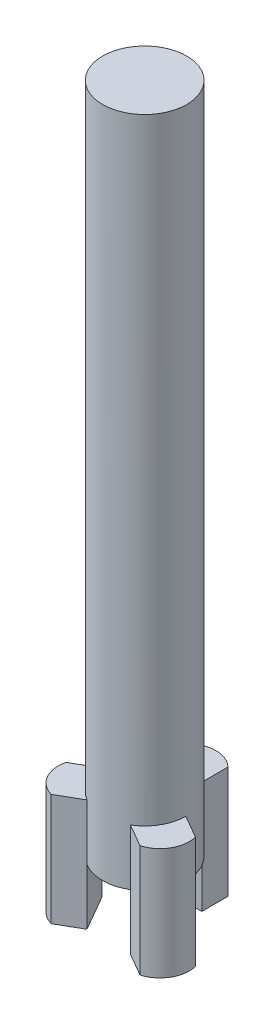
SolidWorks part; units mm, degrees
ref_plane "Plan de face" through (0, 0, 0) normal (0, 0, 1) x (1, 0, 0)
ref_plane "Plan de dessus" through (0, 0, 0) normal (0, 1, 0) x (1, 0, 0)
ref_plane "Plan de droite" through (0, 0, 0) normal (1, 0, 0) x (0, 0, -1)
sketch "Esquisse1" plane through (0, 0, 0) normal (0, 1, 0) x (1, 0, 0)
  circle A0 centre (0, 0) radius 7.5
  dimension "D1" = 15
extrude "Boss.-Extru.1" add sketch "Esquisse1" along normal blind 120 from offset 10
sketch "Esquisse3" plane through (0, 10, 0) normal (0, -1, 0) x (1, 0, 0)
  line L0 (0, 0) -> (0, -7.5) construction
  line L1 (3.6219, -6.5675) -> (-3.6219, -6.5675)
  line L4 (3.6219, -6.5675) -> (3.6219, -11.25)
  line L5 (-3.6219, -6.5675) -> (-3.6219, -11.25)
  circle A0 centre (0, 0) radius 7.5 construction
  arc A4 (3.6219, -11.25) -> (-3.6219, -11.25) centre (0, -7.5) cw
extrude "Boss.-Extru.2" add sketch "Esquisse3" against normal blind 20 from offset 10
pattern_circular "Répétition circulaire1" count 3 over 360 about axis through (0, 0, 0) along (0, 1, 0) of "Boss.-Extru.2"
